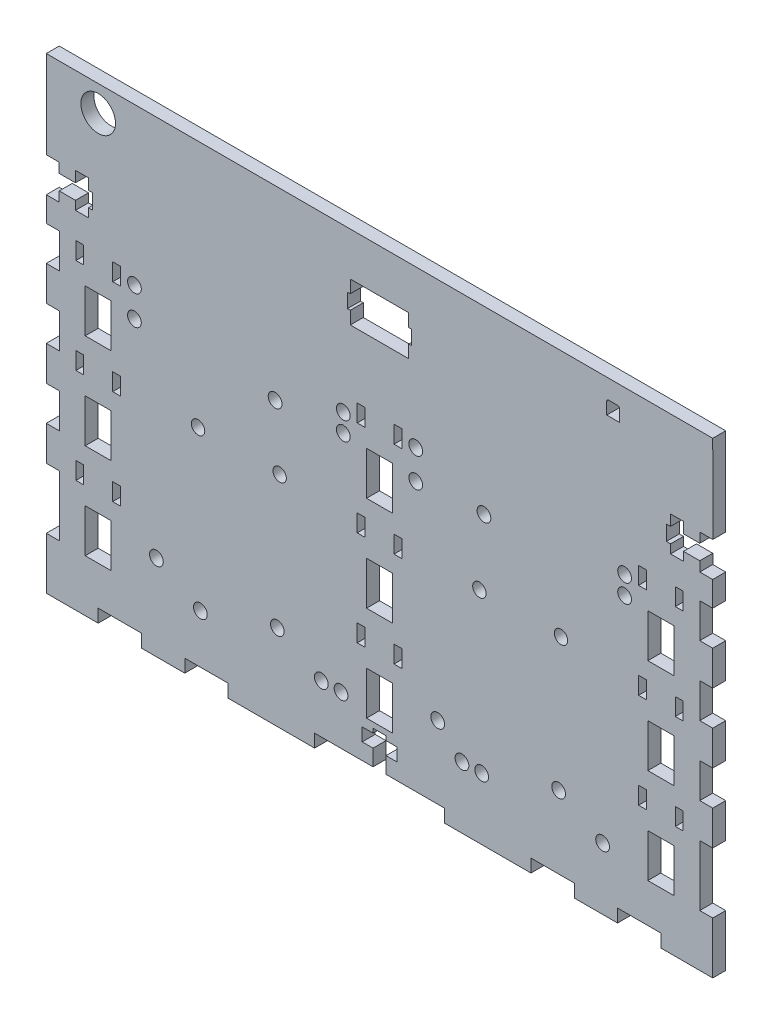
SolidWorks part; units mm, degrees
material "Balsa"
ref_plane "Alzado" through (0, 0, 0) normal (0, 0, 1) x (1, 0, 0)
ref_plane "Planta" through (0, 0, 0) normal (0, 1, 0) x (1, 0, 0)
ref_plane "Vista lateral" through (0, 0, 0) normal (1, 0, 0) x (0, 0, -1)
sketch "Croquis1" plane through (0, 0, 0) normal (0, 0, 1) x (1, 0, 0)
  line L0 (33621.3945, 12954.1794) -> (33621.4126, 12954.1794)
  line L1 (33643.5488, 12968.8076) -> (33643.5488, 12973.6576)
  line L2 (33643.5488, 12973.9576) -> (33643.5488, 12978.8076)
  line L3 (33643.5488, 12978.8076) -> (33646.3988, 12978.8076)
  line L4 (33646.6988, 12978.8076) -> (33649.5488, 12978.8076)
  line L5 (33649.5488, 12978.8076) -> (33649.5488, 12973.9576)
  line L6 (33649.5488, 12973.6576) -> (33649.5488, 12968.8076)
  line L7 (33649.5488, 12968.8076) -> (33646.6988, 12968.8076)
  line L8 (33646.3988, 12968.8076) -> (33643.5488, 12968.8076)
  line L9 (33584.5488, 13000.8076) -> (33584.5488, 12995.9576)
  line L10 (33584.5488, 12995.6576) -> (33584.5488, 12990.8076)
  line L11 (33584.5488, 12990.8076) -> (33581.6988, 12990.8076)
  line L12 (33581.3988, 12990.8076) -> (33578.5488, 12990.8076)
  line L13 (33578.5488, 12990.8076) -> (33578.5488, 12995.6576)
  line L14 (33578.5488, 12995.9576) -> (33578.5488, 13000.8076)
  line L15 (33578.5488, 13000.8076) -> (33581.3988, 13000.8076)
  line L16 (33581.6988, 13000.8076) -> (33584.5488, 13000.8076)
  line L17 (33584.8988, 13008.8076) -> (33585.5512, 13008.8076)
  line L18 (33585.8512, 13008.8076) -> (33586.6988, 13008.8076)
  line L19 (33586.6988, 13008.8076) -> (33586.6988, 13006.8962)
  line L20 (33586.6988, 13006.5962) -> (33586.6988, 13004.8076)
  line L21 (33586.6988, 13004.8076) -> (33585.8512, 13004.8076)
  line L22 (33585.5512, 13004.8076) -> (33584.8988, 13004.8076)
  line L23 (33584.8988, 13004.8076) -> (33584.8988, 13006.5962)
  line L24 (33584.8988, 13006.8962) -> (33584.8988, 13008.8076)
  line L25 (33578.1988, 13004.8076) -> (33577.4254, 13004.8076)
  line L26 (33577.1254, 13004.8076) -> (33576.3988, 13004.8076)
  line L27 (33576.3988, 13004.8076) -> (33576.3988, 13006.7518)
  line L28 (33576.3988, 13007.0518) -> (33576.3988, 13008.8076)
  line L29 (33576.3988, 13008.8076) -> (33577.1254, 13008.8076)
  line L30 (33577.4254, 13008.8076) -> (33578.1988, 13008.8076)
  line L31 (33578.1988, 13008.8076) -> (33578.1988, 13007.0518)
  line L32 (33578.1988, 13006.7518) -> (33578.1988, 13004.8076)
  line L33 (33643.1988, 13004.8076) -> (33642.4254, 13004.8076)
  line L34 (33642.1254, 13004.8076) -> (33641.3988, 13004.8076)
  line L35 (33641.3988, 13004.8076) -> (33641.3988, 13006.7518)
  line L36 (33641.3988, 13007.0518) -> (33641.3988, 13008.8076)
  line L37 (33641.3988, 13008.8076) -> (33642.1254, 13008.8076)
  line L38 (33642.4254, 13008.8076) -> (33643.1988, 13008.8076)
  line L39 (33643.1988, 13008.8076) -> (33643.1988, 13007.0518)
  line L40 (33643.1988, 13006.7518) -> (33643.1988, 13004.8076)
  line L41 (33649.8988, 13008.8076) -> (33650.5512, 13008.8076)
  line L42 (33650.8512, 13008.8076) -> (33651.6988, 13008.8076)
  line L43 (33651.6988, 13008.8076) -> (33651.6988, 13006.8962)
  line L44 (33651.6988, 13006.5962) -> (33651.6988, 13004.8076)
  line L45 (33651.6988, 13004.8076) -> (33650.8512, 13004.8076)
  line L46 (33650.5512, 13004.8076) -> (33649.8988, 13004.8076)
  line L47 (33649.8988, 13004.8076) -> (33649.8988, 13006.5962)
  line L48 (33649.8988, 13006.8962) -> (33649.8988, 13008.8076)
  line L49 (33643.5488, 12990.8076) -> (33643.5488, 12995.6576)
  line L50 (33643.5488, 12995.9576) -> (33643.5488, 13000.8076)
  line L51 (33643.5488, 13000.8076) -> (33646.3988, 13000.8076)
  line L52 (33646.6988, 13000.8076) -> (33649.5488, 13000.8076)
  line L53 (33649.5488, 13000.8076) -> (33649.5488, 12995.9576)
  line L54 (33649.5488, 12995.6576) -> (33649.5488, 12990.8076)
  line L55 (33649.5488, 12990.8076) -> (33646.6988, 12990.8076)
  line L56 (33646.3988, 12990.8076) -> (33643.5488, 12990.8076)
  line L57 (33584.8988, 12986.8076) -> (33585.5512, 12986.8076)
  line L58 (33585.8512, 12986.8076) -> (33586.6988, 12986.8076)
  line L59 (33586.6988, 12986.8076) -> (33586.6988, 12984.8962)
  line L60 (33586.6988, 12984.5962) -> (33586.6988, 12982.8076)
  line L61 (33586.6988, 12982.8076) -> (33585.8512, 12982.8076)
  line L62 (33585.5512, 12982.8076) -> (33584.8988, 12982.8076)
  line L63 (33584.8988, 12982.8076) -> (33584.8988, 12984.5962)
  line L64 (33584.8988, 12984.8962) -> (33584.8988, 12986.8076)
  line L65 (33651.6988, 12960.8076) -> (33650.8512, 12960.8076)
  line L66 (33650.5512, 12960.8076) -> (33649.8988, 12960.8076)
  line L67 (33649.8988, 12960.8076) -> (33649.8988, 12962.5962)
  line L68 (33649.8988, 12962.8962) -> (33649.8988, 12964.8076)
  line L69 (33649.8988, 12964.8076) -> (33650.5512, 12964.8076)
  line L70 (33650.8512, 12964.8076) -> (33651.6988, 12964.8076)
  line L71 (33651.6988, 12964.8076) -> (33651.6988, 12962.8962)
  line L72 (33651.6988, 12962.5962) -> (33651.6988, 12960.8076)
  line L73 (33641.3988, 12964.8076) -> (33642.1254, 12964.8076)
  line L74 (33642.4254, 12964.8076) -> (33643.1988, 12964.8076)
  line L75 (33643.1988, 12964.8076) -> (33643.1988, 12963.0518)
  line L76 (33643.1988, 12962.7518) -> (33643.1988, 12960.8076)
  line L77 (33643.1988, 12960.8076) -> (33642.4254, 12960.8076)
  line L78 (33642.1254, 12960.8076) -> (33641.3988, 12960.8076)
  line L79 (33641.3988, 12960.8076) -> (33641.3988, 12962.7518)
  line L80 (33641.3988, 12963.0518) -> (33641.3988, 12964.8076)
  line L81 (33578.1988, 12982.8076) -> (33577.4254, 12982.8076)
  line L82 (33577.1254, 12982.8076) -> (33576.3988, 12982.8076)
  line L83 (33576.3988, 12982.8076) -> (33576.3988, 12984.7518)
  line L84 (33576.3988, 12985.0518) -> (33576.3988, 12986.8076)
  line L85 (33576.3988, 12986.8076) -> (33577.1254, 12986.8076)
  line L86 (33577.4254, 12986.8076) -> (33578.1988, 12986.8076)
  line L87 (33578.1988, 12986.8076) -> (33578.1988, 12985.0518)
  line L88 (33578.1988, 12984.7518) -> (33578.1988, 12982.8076)
  line L89 (33643.5488, 12956.8076) -> (33646.3988, 12956.8076)
  line L90 (33646.6988, 12956.8076) -> (33649.5488, 12956.8076)
  line L91 (33649.5488, 12956.8076) -> (33649.5488, 12951.9576)
  line L92 (33649.5488, 12951.6576) -> (33649.5488, 12946.8076)
  line L93 (33649.5488, 12946.8076) -> (33646.6988, 12946.8076)
  line L94 (33646.3988, 12946.8076) -> (33643.5488, 12946.8076)
  line L95 (33643.5488, 12946.8076) -> (33643.5488, 12951.6576)
  line L96 (33643.5488, 12951.9576) -> (33643.5488, 12956.8076)
  line L97 (33708.1988, 12960.8076) -> (33707.4254, 12960.8076)
  line L98 (33707.1254, 12960.8076) -> (33706.3988, 12960.8076)
  line L99 (33706.3988, 12960.8076) -> (33706.3988, 12962.7518)
  line L100 (33706.3988, 12963.0518) -> (33706.3988, 12964.8076)
  line L101 (33706.3988, 12964.8076) -> (33707.1254, 12964.8076)
  line L102 (33707.4254, 12964.8076) -> (33708.1988, 12964.8076)
  line L103 (33708.1988, 12964.8076) -> (33708.1988, 12963.0518)
  line L104 (33708.1988, 12962.7518) -> (33708.1988, 12960.8076)
  line L105 (33584.5488, 12946.8076) -> (33581.5488, 12946.8076)
  line L106 (33581.4403, 12946.8076) -> (33578.5488, 12946.8076)
  line L107 (33578.5488, 12946.8076) -> (33578.5488, 12951.7169)
  line L108 (33578.5488, 12951.8983) -> (33578.5488, 12956.8076)
  line L109 (33578.5488, 12956.8076) -> (33581.4403, 12956.8076)
  line L110 (33581.5488, 12956.8076) -> (33584.5488, 12956.8076)
  line L111 (33584.5488, 12956.8076) -> (33584.5488, 12951.8983)
  line L112 (33584.5488, 12951.7169) -> (33584.5488, 12946.8076)
  line L113 (33584.8988, 12964.8076) -> (33585.5512, 12964.8076)
  line L114 (33585.8512, 12964.8076) -> (33586.6988, 12964.8076)
  line L115 (33586.6988, 12964.8076) -> (33586.6988, 12962.8962)
  line L116 (33586.6988, 12962.5962) -> (33586.6988, 12960.8076)
  line L117 (33586.6988, 12960.8076) -> (33585.8512, 12960.8076)
  line L118 (33585.5512, 12960.8076) -> (33584.8988, 12960.8076)
  line L119 (33584.8988, 12960.8076) -> (33584.8988, 12962.5962)
  line L120 (33584.8988, 12962.8962) -> (33584.8988, 12964.8076)
  line L121 (33708.5488, 12956.8076) -> (33711.3988, 12956.8076)
  line L122 (33711.6988, 12956.8076) -> (33714.5488, 12956.8076)
  line L123 (33714.5488, 12956.8076) -> (33714.5488, 12951.9576)
  line L124 (33714.5488, 12951.6576) -> (33714.5488, 12946.8076)
  line L125 (33714.5488, 12946.8076) -> (33711.6988, 12946.8076)
  line L126 (33711.3988, 12946.8076) -> (33708.5488, 12946.8076)
  line L127 (33708.5488, 12946.8076) -> (33708.5488, 12951.6576)
  line L128 (33708.5488, 12951.9576) -> (33708.5488, 12956.8076)
  line L129 (33578.1988, 12960.8076) -> (33577.4254, 12960.8076)
  line L130 (33577.1254, 12960.8076) -> (33576.3988, 12960.8076)
  line L131 (33576.3988, 12960.8076) -> (33576.3988, 12962.7518)
  line L132 (33576.3988, 12963.0518) -> (33576.3988, 12964.8076)
  line L133 (33576.3988, 12964.8076) -> (33577.1254, 12964.8076)
  line L134 (33577.4254, 12964.8076) -> (33578.1988, 12964.8076)
  line L135 (33578.1988, 12964.8076) -> (33578.1988, 12963.0518)
  line L136 (33578.1988, 12962.7518) -> (33578.1988, 12960.8076)
  line L137 (33714.8988, 12964.8076) -> (33715.5512, 12964.8076)
  line L138 (33715.8512, 12964.8076) -> (33716.6988, 12964.8076)
  line L139 (33716.6988, 12964.8076) -> (33716.6988, 12962.8962)
  line L140 (33716.6988, 12962.5962) -> (33716.6988, 12960.8076)
  line L141 (33716.6988, 12960.8076) -> (33715.8512, 12960.8076)
  line L142 (33715.5512, 12960.8076) -> (33714.8988, 12960.8076)
  line L143 (33714.8988, 12960.8076) -> (33714.8988, 12962.5962)
  line L144 (33714.8988, 12962.8962) -> (33714.8988, 12964.8076)
  line L145 (33723.5488, 12976.8076) -> (33720.5488, 12976.8076)
  line L146 (33723.5488, 12984.8076) -> (33723.5488, 12976.8076)
  line L147 (33723.5488, 12984.8076) -> (33720.5488, 12984.8076)
  line L148 (33720.5488, 12984.8076) -> (33720.5488, 12992.8076)
  line L149 (33572.5488, 12976.8076) -> (33572.5488, 12968.8076)
  line L150 (33723.5488, 12992.8076) -> (33720.5488, 12992.8076)
  line L151 (33723.5488, 13000.8076) -> (33723.5488, 12992.8076)
  line L152 (33723.5488, 13000.8076) -> (33720.5488, 13000.8076)
  line L153 (33720.5488, 13000.8076) -> (33720.5488, 13008.8076)
  line L154 (33723.5488, 13008.8076) -> (33720.5488, 13008.8076)
  line L155 (33723.5488, 13014.5511) -> (33723.5488, 13008.8076)
  line L156 (33723.5503, 13022.5518) -> (33723.5488, 13042.8076)
  line L157 (33569.5488, 13042.8076) -> (33723.5488, 13042.8076)
  line L158 (33572.5488, 13000.8076) -> (33572.5488, 13008.8076)
  line L159 (33569.5488, 13000.8076) -> (33572.5488, 13000.8076)
  line L160 (33569.5488, 13000.8076) -> (33569.5488, 12992.8076)
  line L161 (33569.5488, 12992.8076) -> (33572.5488, 12992.8076)
  line L162 (33572.5488, 12984.8076) -> (33572.5488, 12992.8076)
  line L163 (33572.5484, 13014.5511) -> (33572.5481, 13016.8076)
  line L164 (33569.5488, 12984.8076) -> (33572.5488, 12984.8076)
  line L165 (33569.5488, 12984.8076) -> (33569.5488, 12976.8076)
  line L166 (33569.5488, 12976.8076) -> (33572.5488, 12976.8076)
  line L167 (33572.5488, 12960.8076) -> (33572.5488, 12946.8076)
  line L168 (33601.5488, 12937.8076) -> (33611.5488, 12937.8076)
  line L169 (33569.5488, 12968.8076) -> (33572.5488, 12968.8076)
  line L170 (33569.5488, 12968.8076) -> (33569.5488, 12960.8076)
  line L171 (33569.5488, 12960.8076) -> (33572.5488, 12960.8076)
  line L172 (33681.665, 12937.8076) -> (33681.965, 12937.8076)
  line L174 (33569.5488, 12946.8076) -> (33572.5488, 12946.8076)
  line L175 (33569.5488, 12946.8076) -> (33569.5488, 12934.8076)
  line L176 (33569.5488, 12934.8076) -> (33581.5488, 12934.8076)
  line L177 (33581.5488, 12934.8076) -> (33581.5488, 12937.8076)
  line L178 (33591.5488, 12937.8076) -> (33581.5488, 12937.8076)
  line L179 (33591.5488, 12934.8076) -> (33591.5488, 12937.8076)
  line L180 (33591.5488, 12934.8076) -> (33601.5488, 12934.8076)
  line L181 (33601.5488, 12934.8076) -> (33601.5488, 12937.8076)
  line L184 (33631.5488, 12934.8076) -> (33631.5488, 12937.8076)
  line L187 (33661.5488, 12934.8076) -> (33661.5488, 12937.8076)
  line L188 (33645.0488, 12937.8076) -> (33645.0488, 12941.5576)
  line L189 (33645.0488, 12941.5576) -> (33642.5488, 12941.5576)
  line L190 (33642.5488, 12941.5576) -> (33642.5488, 12944.5576)
  line L191 (33645.0488, 12944.5576) -> (33642.5488, 12944.5576)
  line L192 (33645.0488, 12944.5576) -> (33645.0488, 12945.5376)
  line L193 (33648.0488, 12945.5376) -> (33645.0488, 12945.5376)
  line L194 (33648.0488, 12944.5576) -> (33648.0488, 12945.5376)
  line L195 (33650.5488, 12944.5576) -> (33648.0488, 12944.5576)
  line L196 (33650.5488, 12941.5576) -> (33650.5488, 12944.5576)
  line L197 (33650.5488, 12941.5576) -> (33648.0488, 12941.5576)
  line L198 (33648.0488, 12937.8076) -> (33648.0488, 12941.5576)
  line L199 (33681.5488, 12937.8076) -> (33681.665, 12937.8076)
  line L200 (33681.965, 12937.8076) -> (33691.5488, 12937.8076)
  line L201 (33691.5488, 12934.8076) -> (33691.5488, 12937.8076)
  line L202 (33691.5488, 12934.8076) -> (33701.5488, 12934.8076)
  line L203 (33701.5488, 12934.8076) -> (33701.5488, 12937.8076)
  line L204 (33701.5488, 12937.8076) -> (33711.5488, 12937.8076)
  line L205 (33711.5488, 12934.8076) -> (33711.5488, 12937.8076)
  line L206 (33711.5488, 12934.8076) -> (33723.5488, 12934.8076)
  line L207 (33723.5488, 12946.8076) -> (33723.5488, 12934.8076)
  line L208 (33723.5488, 12946.8076) -> (33720.5488, 12946.8076)
  line L209 (33720.5488, 12960.8076) -> (33720.5488, 12952.7511)
  line L210 (33720.5488, 12952.4511) -> (33720.5488, 12946.8076)
  line L211 (33723.5488, 12960.8076) -> (33720.5488, 12960.8076)
  line L212 (33723.5488, 12968.8076) -> (33723.5488, 12960.8076)
  line L213 (33723.5488, 12968.8076) -> (33720.5488, 12968.8076)
  line L214 (33702.0488, 13037.9076) -> (33702.0488, 13035.2076)
  line L215 (33699.0488, 13035.2076) -> (33702.0488, 13035.2076)
  line L216 (33699.0488, 13037.9076) -> (33699.0488, 13035.2076)
  line L217 (33699.5488, 13038.4076) -> (33701.5488, 13038.4076)
  line L218 (33639.7988, 13032.8076) -> (33653.2988, 13032.8076)
  line L219 (33653.2988, 13032.8076) -> (33653.2988, 13029.8576)
  line L220 (33653.2988, 13029.8576) -> (33653.9488, 13029.8576)
  line L221 (33653.9488, 13029.8576) -> (33653.9488, 13026.5576)
  line L222 (33653.2988, 13026.5576) -> (33653.9488, 13026.5576)
  line L223 (33653.2988, 13026.5576) -> (33653.2988, 13023.6076)
  line L224 (33639.7988, 13023.6076) -> (33653.2988, 13023.6076)
  line L225 (33639.7988, 13026.5576) -> (33639.7988, 13023.6076)
  line L226 (33639.1488, 13026.5576) -> (33639.7988, 13026.5576)
  line L227 (33639.1488, 13029.8576) -> (33639.1488, 13026.5576)
  line L228 (33639.1488, 13029.8576) -> (33639.7988, 13029.8576)
  line L229 (33639.7988, 13032.8076) -> (33639.7988, 13029.8576)
  line L230 (33611.5488, 12937.8076) -> (33611.5488, 12934.8076)
  line L231 (33611.5488, 12934.8076) -> (33631.5488, 12934.8076)
  line L232 (33631.5488, 12937.8076) -> (33645.0488, 12937.8076)
  line L233 (33648.0488, 12937.8076) -> (33661.5488, 12937.8076)
  line L234 (33681.5488, 12934.8076) -> (33681.5488, 12937.8076)
  line L235 (33681.5488, 12934.8076) -> (33661.5488, 12934.8076)
  line L237 (33578.5488, 12968.8076) -> (33578.5488, 12973.6576)
  line L238 (33578.5488, 12973.9576) -> (33578.5488, 12978.8076)
  line L239 (33578.5488, 12978.8076) -> (33581.3988, 12978.8076)
  line L240 (33581.6988, 12978.8076) -> (33584.5488, 12978.8076)
  line L241 (33584.5488, 12978.8076) -> (33584.5488, 12973.9576)
  line L242 (33584.5488, 12973.6576) -> (33584.5488, 12968.8076)
  line L243 (33584.5488, 12968.8076) -> (33581.6988, 12968.8076)
  line L244 (33581.3988, 12968.8076) -> (33578.5488, 12968.8076)
  line L245 (33649.8988, 12986.8076) -> (33650.5512, 12986.8076)
  line L246 (33650.8512, 12986.8076) -> (33651.6988, 12986.8076)
  line L247 (33651.6988, 12986.8076) -> (33651.6988, 12984.8962)
  line L248 (33651.6988, 12984.5962) -> (33651.6988, 12982.8076)
  line L249 (33651.6988, 12982.8076) -> (33650.8512, 12982.8076)
  line L250 (33650.5512, 12982.8076) -> (33649.8988, 12982.8076)
  line L251 (33649.8988, 12982.8076) -> (33649.8988, 12984.5962)
  line L252 (33649.8988, 12984.8962) -> (33649.8988, 12986.8076)
  line L253 (33643.1988, 12982.8076) -> (33642.4254, 12982.8076)
  line L254 (33642.1254, 12982.8076) -> (33641.3988, 12982.8076)
  line L255 (33641.3988, 12982.8076) -> (33641.3988, 12984.7518)
  line L256 (33641.3988, 12985.0518) -> (33641.3988, 12986.8076)
  line L257 (33641.3988, 12986.8076) -> (33642.1254, 12986.8076)
  line L258 (33642.4254, 12986.8076) -> (33643.1988, 12986.8076)
  line L259 (33643.1988, 12986.8076) -> (33643.1988, 12985.0518)
  line L260 (33643.1988, 12984.7518) -> (33643.1988, 12982.8076)
  line L261 (33720.5488, 12968.8076) -> (33720.5488, 12976.8076)
  line L286 (33714.8988, 12986.8076) -> (33715.5512, 12986.8076)
  line L287 (33715.8512, 12986.8076) -> (33716.6988, 12986.8076)
  line L288 (33716.6988, 12986.8076) -> (33716.6988, 12984.8962)
  line L289 (33716.6988, 12984.5962) -> (33716.6988, 12982.8076)
  line L290 (33716.6988, 12982.8076) -> (33715.8512, 12982.8076)
  line L291 (33715.5512, 12982.8076) -> (33714.8988, 12982.8076)
  line L292 (33714.8988, 12982.8076) -> (33714.8988, 12984.5962)
  line L293 (33714.8988, 12984.8962) -> (33714.8988, 12986.8076)
  line L294 (33708.1988, 12982.8076) -> (33707.4254, 12982.8076)
  line L295 (33707.1254, 12982.8076) -> (33706.3988, 12982.8076)
  line L296 (33706.3988, 12982.8076) -> (33706.3988, 12984.7518)
  line L297 (33706.3988, 12985.0518) -> (33706.3988, 12986.8076)
  line L298 (33706.3988, 12986.8076) -> (33707.1254, 12986.8076)
  line L299 (33707.4254, 12986.8076) -> (33708.1988, 12986.8076)
  line L300 (33708.1988, 12986.8076) -> (33708.1988, 12985.0518)
  line L301 (33708.1988, 12984.7518) -> (33708.1988, 12982.8076)
  line L302 (33708.5488, 12968.8076) -> (33708.5488, 12973.6576)
  line L303 (33708.5488, 12973.9576) -> (33708.5488, 12978.8076)
  line L304 (33708.5488, 12978.8076) -> (33711.3988, 12978.8076)
  line L305 (33711.6988, 12978.8076) -> (33714.5488, 12978.8076)
  line L306 (33714.5488, 12978.8076) -> (33714.5488, 12973.9576)
  line L307 (33714.5488, 12973.6576) -> (33714.5488, 12968.8076)
  line L308 (33714.5488, 12968.8076) -> (33711.6988, 12968.8076)
  line L309 (33711.3988, 12968.8076) -> (33708.5488, 12968.8076)
  line L310 (33720.5495, 13020.3018) -> (33720.5498, 13022.5518)
  line L311 (33720.5493, 13014.5511) -> (33720.5495, 13016.8076)
  line L313 (33723.5488, 13014.5511) -> (33720.5493, 13014.5511)
  line L315 (33723.5503, 13022.5518) -> (33720.5498, 13022.5518)
  line L316 (33720.5495, 13020.3018) -> (33716.7995, 13020.3018)
  line L317 (33716.7995, 13022.7997) -> (33716.7995, 13020.3018)
  line L318 (33716.7995, 13022.7997) -> (33713.7995, 13022.7997)
  line L319 (33713.7995, 13022.7997) -> (33713.7995, 13020.3018)
  line L320 (33713.7995, 13020.3018) -> (33712.8195, 13020.3018)
  line L321 (33712.8195, 13020.3018) -> (33712.8195, 13016.8076)
  line L322 (33713.7995, 13016.8076) -> (33712.8195, 13016.8076)
  line L323 (33713.7995, 13016.8076) -> (33713.7995, 13014.7997)
  line L324 (33716.7995, 13014.7997) -> (33713.7995, 13014.7997)
  line L325 (33716.7995, 13016.8076) -> (33716.7995, 13014.7997)
  line L326 (33720.5495, 13016.8076) -> (33716.7995, 13016.8076)
  line L328 (33569.5488, 13008.8076) -> (33572.5488, 13008.8076)
  line L329 (33569.5488, 13014.5511) -> (33569.5488, 13008.8076)
  line L330 (33569.5488, 13042.8076) -> (33569.5474, 13022.5518)
  line L332 (33572.5481, 13020.3018) -> (33572.5478, 13022.5518)
  line L334 (33569.5488, 13014.5511) -> (33572.5484, 13014.5511)
  line L336 (33569.5474, 13022.5518) -> (33572.5478, 13022.5518)
  line L337 (33572.5481, 13020.3018) -> (33576.2981, 13020.3018)
  line L338 (33576.2981, 13022.7997) -> (33576.2981, 13020.3018)
  line L339 (33576.2981, 13022.7997) -> (33579.2981, 13022.7997)
  line L340 (33579.2981, 13022.7997) -> (33579.2981, 13020.3018)
  line L341 (33579.2981, 13020.3018) -> (33580.2781, 13020.3018)
  line L342 (33580.2781, 13020.3018) -> (33580.2781, 13016.8076)
  line L343 (33579.2981, 13016.8076) -> (33580.2781, 13016.8076)
  line L344 (33579.2981, 13016.8076) -> (33579.2981, 13014.7997)
  line L345 (33576.2981, 13014.7997) -> (33579.2981, 13014.7997)
  line L346 (33576.2981, 13016.8076) -> (33576.2981, 13014.7997)
  line L347 (33572.5481, 13016.8076) -> (33576.2981, 13016.8076)
  line L349 (33576.3988, 13004.8076) -> (33578.1988, 13004.8076)
  line L350 (33578.1988, 13004.8076) -> (33578.1988, 13008.8076)
  line L351 (33578.1988, 13008.8076) -> (33576.3988, 13008.8076)
  line L352 (33576.3988, 13008.8076) -> (33576.3988, 13004.8076)
  line L353 (33584.8988, 13004.8076) -> (33586.6988, 13004.8076)
  line L354 (33586.6988, 13004.8076) -> (33586.6988, 13008.8076)
  line L355 (33586.6988, 13008.8076) -> (33584.8988, 13008.8076)
  line L356 (33584.8988, 13008.8076) -> (33584.8988, 13004.8076)
  line L357 (33578.5488, 12990.8076) -> (33584.5488, 12990.8076)
  line L358 (33584.5488, 12990.8076) -> (33584.5488, 13000.8076)
  line L359 (33584.5488, 13000.8076) -> (33578.5488, 13000.8076)
  line L360 (33578.5488, 13000.8076) -> (33578.5488, 12990.8076)
  line L361 (33576.3988, 12982.8076) -> (33578.1988, 12982.8076)
  line L362 (33578.1988, 12982.8076) -> (33578.1988, 12986.8076)
  line L363 (33578.1988, 12986.8076) -> (33576.3988, 12986.8076)
  line L364 (33576.3988, 12986.8076) -> (33576.3988, 12982.8076)
  line L365 (33584.8988, 12982.8076) -> (33586.6988, 12982.8076)
  line L366 (33586.6988, 12982.8076) -> (33586.6988, 12986.8076)
  line L367 (33586.6988, 12986.8076) -> (33584.8988, 12986.8076)
  line L368 (33584.8988, 12986.8076) -> (33584.8988, 12982.8076)
  line L369 (33578.5488, 12968.8076) -> (33584.5488, 12968.8076)
  line L370 (33584.5488, 12968.8076) -> (33584.5488, 12978.8076)
  line L371 (33584.5488, 12978.8076) -> (33578.5488, 12978.8076)
  line L372 (33578.5488, 12978.8076) -> (33578.5488, 12968.8076)
  line L373 (33576.3988, 12960.8076) -> (33578.1988, 12960.8076)
  line L374 (33578.1988, 12960.8076) -> (33578.1988, 12964.8076)
  line L375 (33578.1988, 12964.8076) -> (33576.3988, 12964.8076)
  line L376 (33576.3988, 12964.8076) -> (33576.3988, 12960.8076)
  line L377 (33584.8988, 12960.8076) -> (33586.6988, 12960.8076)
  line L378 (33586.6988, 12960.8076) -> (33586.6988, 12964.8076)
  line L379 (33586.6988, 12964.8076) -> (33584.8988, 12964.8076)
  line L380 (33584.8988, 12964.8076) -> (33584.8988, 12960.8076)
  line L381 (33578.5488, 12956.8076) -> (33584.5488, 12956.8076)
  line L382 (33584.5488, 12956.8076) -> (33584.5488, 12946.8076)
  line L383 (33584.5488, 12946.8076) -> (33578.5488, 12946.8076)
  line L384 (33578.5488, 12946.8076) -> (33578.5488, 12956.8076)
  line L388 (33720.5488, 12952.4511) -> (33720.5488, 12952.7511)
  line L390 (33641.3988, 13004.8076) -> (33643.1988, 13004.8076)
  line L391 (33643.1988, 13004.8076) -> (33643.1988, 13008.8076)
  line L392 (33643.1988, 13008.8076) -> (33641.3988, 13008.8076)
  line L393 (33641.3988, 13008.8076) -> (33641.3988, 13004.8076)
  line L394 (33649.8988, 13004.8076) -> (33651.6988, 13004.8076)
  line L395 (33651.6988, 13004.8076) -> (33651.6988, 13008.8076)
  line L396 (33651.6988, 13008.8076) -> (33649.8988, 13008.8076)
  line L397 (33649.8988, 13008.8076) -> (33649.8988, 13004.8076)
  line L398 (33643.5488, 12990.8076) -> (33649.5488, 12990.8076)
  line L399 (33649.5488, 12990.8076) -> (33649.5488, 13000.8076)
  line L400 (33649.5488, 13000.8076) -> (33643.5488, 13000.8076)
  line L401 (33643.5488, 13000.8076) -> (33643.5488, 12990.8076)
  line L402 (33641.3988, 12982.8076) -> (33643.1988, 12982.8076)
  line L403 (33643.1988, 12982.8076) -> (33643.1988, 12986.8076)
  line L404 (33643.1988, 12986.8076) -> (33641.3988, 12986.8076)
  line L405 (33641.3988, 12986.8076) -> (33641.3988, 12982.8076)
  line L406 (33649.8988, 12982.8076) -> (33651.6988, 12982.8076)
  line L407 (33651.6988, 12982.8076) -> (33651.6988, 12986.8076)
  line L408 (33651.6988, 12986.8076) -> (33649.8988, 12986.8076)
  line L409 (33649.8988, 12986.8076) -> (33649.8988, 12982.8076)
  line L410 (33643.5488, 12968.8076) -> (33649.5488, 12968.8076)
  line L411 (33649.5488, 12968.8076) -> (33649.5488, 12978.8076)
  line L412 (33649.5488, 12978.8076) -> (33643.5488, 12978.8076)
  line L413 (33643.5488, 12978.8076) -> (33643.5488, 12968.8076)
  line L414 (33641.3988, 12960.8076) -> (33643.1988, 12960.8076)
  line L415 (33643.1988, 12960.8076) -> (33643.1988, 12964.8076)
  line L416 (33643.1988, 12964.8076) -> (33641.3988, 12964.8076)
  line L417 (33641.3988, 12964.8076) -> (33641.3988, 12960.8076)
  line L418 (33649.8988, 12960.8076) -> (33651.6988, 12960.8076)
  line L419 (33651.6988, 12960.8076) -> (33651.6988, 12964.8076)
  line L420 (33651.6988, 12964.8076) -> (33649.8988, 12964.8076)
  line L421 (33649.8988, 12964.8076) -> (33649.8988, 12960.8076)
  line L422 (33643.5488, 12946.8076) -> (33649.5488, 12946.8076)
  line L423 (33649.5488, 12946.8076) -> (33649.5488, 12956.8076)
  line L424 (33649.5488, 12956.8076) -> (33643.5488, 12956.8076)
  line L425 (33643.5488, 12956.8076) -> (33643.5488, 12946.8076)
  line L426 (33706.3988, 13004.8076) -> (33708.1988, 13004.8076)
  line L427 (33708.1988, 13004.8076) -> (33708.1988, 13008.8076)
  line L428 (33708.1988, 13008.8076) -> (33706.3988, 13008.8076)
  line L429 (33706.3988, 13008.8076) -> (33706.3988, 13004.8076)
  line L430 (33714.8988, 13004.8076) -> (33716.6988, 13004.8076)
  line L431 (33716.6988, 13004.8076) -> (33716.6988, 13008.8076)
  line L432 (33716.6988, 13008.8076) -> (33714.8988, 13008.8076)
  line L433 (33714.8988, 13008.8076) -> (33714.8988, 13004.8076)
  line L434 (33708.5488, 12990.8076) -> (33714.5488, 12990.8076)
  line L435 (33714.5488, 12990.8076) -> (33714.5488, 13000.8076)
  line L436 (33714.5488, 13000.8076) -> (33708.5488, 13000.8076)
  line L437 (33708.5488, 13000.8076) -> (33708.5488, 12990.8076)
  line L438 (33706.3988, 12982.8076) -> (33708.1988, 12982.8076)
  line L439 (33708.1988, 12982.8076) -> (33708.1988, 12986.8076)
  line L440 (33708.1988, 12986.8076) -> (33706.3988, 12986.8076)
  line L441 (33706.3988, 12986.8076) -> (33706.3988, 12982.8076)
  line L442 (33714.8988, 12982.8076) -> (33716.6988, 12982.8076)
  line L443 (33716.6988, 12982.8076) -> (33716.6988, 12986.8076)
  line L444 (33716.6988, 12986.8076) -> (33714.8988, 12986.8076)
  line L445 (33714.8988, 12986.8076) -> (33714.8988, 12982.8076)
  line L446 (33708.5488, 12968.8076) -> (33714.5488, 12968.8076)
  line L447 (33714.5488, 12968.8076) -> (33714.5488, 12978.8076)
  line L448 (33714.5488, 12978.8076) -> (33708.5488, 12978.8076)
  line L449 (33708.5488, 12978.8076) -> (33708.5488, 12968.8076)
  line L450 (33714.8988, 12960.8076) -> (33716.6988, 12960.8076)
  line L451 (33716.6988, 12960.8076) -> (33716.6988, 12964.8076)
  line L452 (33716.6988, 12964.8076) -> (33714.8988, 12964.8076)
  line L453 (33714.8988, 12964.8076) -> (33714.8988, 12960.8076)
  line L454 (33706.3988, 12960.8076) -> (33708.1988, 12960.8076)
  line L455 (33708.1988, 12960.8076) -> (33708.1988, 12964.8076)
  line L456 (33708.1988, 12964.8076) -> (33706.3988, 12964.8076)
  line L457 (33706.3988, 12964.8076) -> (33706.3988, 12960.8076)
  line L458 (33708.5488, 12946.8076) -> (33714.5488, 12946.8076)
  line L459 (33714.5488, 12946.8076) -> (33714.5488, 12956.8076)
  line L460 (33714.5488, 12956.8076) -> (33708.5488, 12956.8076)
  line L461 (33708.5488, 12956.8076) -> (33708.5488, 12946.8076)
  arc A0 (33605.973, 12950.4404) -> (33606.2022, 12947.8811) centre (33605.1588, 12949.0776) ccw
  arc A1 (33606.4094, 12948.0998) -> (33606.2077, 12950.2693) centre (33605.1588, 12949.0776) ccw
  arc A2 (33638.5927, 12950.3614) -> (33638.7862, 12947.9599) centre (33637.6588, 12949.0776) ccw
  arc A3 (33638.9813, 12948.1994) -> (33638.8138, 12950.1667) centre (33637.6588, 12949.0776) ccw
  arc A4 (33666.5087, 12950.3785) -> (33664.0223, 12948.8913) centre (33665.5988, 12949.0776) ccw
  arc A5 (33666.7818, 12948.019) -> (33666.7326, 12950.1888) centre (33665.5988, 12949.0776) ccw
  arc A6 (33664.0841, 12948.6025) -> (33666.5646, 12947.8176) centre (33665.5988, 12949.0776) ccw
  arc A7 (33671.4312, 13002.5455) -> (33669.0968, 13001.0157) centre (33670.6788, 13001.1476) ccw
  arc A8 (33671.7672, 12999.9919) -> (33671.6724, 13002.3857) centre (33670.6788, 13001.1476) ccw
  arc A9 (33669.1481, 13000.7269) -> (33671.5374, 12999.8123) centre (33670.6788, 13001.1476) ccw
  arc A12 (33670.546, 12950.6171) -> (33668.5996, 12949.3759) centre (33670.1588, 12949.0776) ccw
  arc A13 (33671.2791, 12947.9528) -> (33670.823, 12950.5194) centre (33670.1588, 12949.0776) ccw
  arc A14 (33668.5714, 12949.0871) -> (33671.0534, 12947.7661) centre (33670.1588, 12949.0776) ccw
  arc A15 (33698.9811, 12950.3973) -> (33699.1028, 12947.8479) centre (33698.0988, 12949.0776) ccw
  arc A16 (33699.3152, 12948.0575) -> (33699.2082, 12950.2131) centre (33698.0988, 12949.0776) ccw
  arc A17 (33633.9904, 12950.3911) -> (33631.5223, 12948.8913) centre (33633.0988, 12949.0776) ccw
  arc A18 (33634.2662, 12948.0017) -> (33634.2164, 12950.205) centre (33633.0988, 12949.0776) ccw
  arc A19 (33631.5841, 12948.6025) -> (33634.0468, 12947.8042) centre (33633.0988, 12949.0776) ccw
  arc A20 (33655.7902, 13001.2046) -> (33655.9837, 12998.7002) centre (33654.9188, 12999.8776) ccw
  arc A21 (33656.1879, 12998.9239) -> (33656.0185, 13001.0225) centre (33654.9188, 12999.8776) ccw
  arc A22 (33639.4222, 13000.1606) -> (33639.3253, 13002.2457) centre (33638.1788, 13001.1476) ccw
  arc A23 (33639.103, 13002.4383) -> (33639.2139, 12999.9439) centre (33638.1788, 13001.1476) ccw
  arc A24 (33590.8435, 13001.168) -> (33591.1007, 12998.8177) centre (33589.9188, 12999.8776) ccw
  arc A25 (33591.287, 12999.0725) -> (33591.0657, 13000.9752) centre (33589.9188, 12999.8776) ccw
  arc A29 (33689.2053, 12986.9041) -> (33686.9249, 12985.4809) centre (33688.4738, 12985.5376) ccw
  arc A30 (33689.5962, 12984.4686) -> (33689.4466, 12986.7443) centre (33688.4738, 12985.5376) ccw
  arc A31 (33686.9628, 12985.1922) -> (33689.3741, 12984.2758) centre (33688.4738, 12985.5376) ccw
  arc A32 (33670.8945, 12984.6499) -> (33670.6752, 12986.6765) centre (33669.6238, 12985.5376) ccw
  arc A33 (33670.4436, 12986.853) -> (33670.6952, 12984.4175) centre (33669.6238, 12985.5376) ccw
  arc A34 (33624.2777, 12986.8628) -> (33621.9344, 12985.3567) centre (33623.4738, 12985.5376) ccw
  arc A35 (33624.5666, 12984.4383) -> (33624.511, 12986.6894) centre (33623.4738, 12985.5376) ccw
  arc A36 (33621.9967, 12985.068) -> (33624.3404, 12984.2524) centre (33623.4738, 12985.5376) ccw
  arc A37 (33605.3074, 12986.9287) -> (33603.0785, 12985.6576) centre (33604.6238, 12985.5376) ccw
  arc A38 (33605.8317, 12984.5662) -> (33605.5536, 12986.7777) centre (33604.6238, 12985.5376) ccw
  arc A39 (33603.083, 12985.3688) -> (33605.622, 12984.3518) centre (33604.6238, 12985.5376) ccw
  arc A40 (33595.54, 12956.06) -> (33593.4114, 12954.5788) centre (33594.9988, 12954.5676) ccw
  arc A41 (33596.0207, 12953.3527) -> (33595.8023, 12955.9368) centre (33594.9988, 12954.5676) ccw
  arc A42 (33593.4358, 12954.29) -> (33595.7829, 12953.1872) centre (33594.9988, 12954.5676) ccw
  arc A43 (33655.7879, 13007.9661) -> (33653.3446, 13006.4324) centre (33654.9188, 13006.6376) ccw
  arc A44 (33656.0532, 13005.527) -> (33656.0165, 13007.7844) centre (33654.9188, 13006.6376) ccw
  arc A45 (33653.4101, 13006.1436) -> (33655.8294, 13005.3372) centre (33654.9188, 13006.6376) ccw
  arc A46 (33590.6918, 13008.0242) -> (33588.3323, 13006.6928) centre (33589.9188, 13006.6376) ccw
  arc A47 (33591.1569, 13005.6439) -> (33590.9309, 13007.8607) centre (33589.9188, 13006.6376) ccw
  arc A48 (33588.3486, 13006.404) -> (33590.9477, 13005.4286) centre (33589.9188, 13006.6376) ccw
  arc A49 (33639.0249, 13006.7108) -> (33636.605, 13005.1594) centre (33638.1788, 13005.3676) ccw
  arc A50 (33639.2911, 13004.2348) -> (33639.2561, 13006.5336) centre (33638.1788, 13005.3676) ccw
  arc A51 (33636.6711, 13004.8706) -> (33639.0643, 13004.05) centre (33638.1788, 13005.3676) ccw
  arc A55 (33688.8269, 12955.8834) -> (33689.0887, 12953.4731) centre (33687.9388, 12954.5676) ccw
  arc A56 (33689.2804, 12953.7188) -> (33689.0534, 12955.6981) centre (33687.9388, 12954.5676) ccw
  arc A57 (33660.876, 12955.8907) -> (33658.4199, 12954.4031) centre (33659.9988, 12954.5676) ccw
  arc A58 (33661.1694, 12953.4952) -> (33661.1037, 12955.7075) centre (33659.9988, 12954.5676) ccw
  arc A59 (33658.4774, 12954.1143) -> (33660.9504, 12953.2969) centre (33659.9988, 12954.5676) ccw
  arc A60 (33623.7996, 12955.8864) -> (33621.3671, 12954.4682) centre (33622.9388, 12954.5676) ccw
  arc A61 (33624.1397, 12953.5488) -> (33624.0282, 12955.7048) centre (33622.9388, 12954.5676) ccw
  arc A62 (33621.4126, 12954.1794) -> (33623.9263, 12953.3408) centre (33622.9388, 12954.5676) ccw
  circle A63 centre (33581.5488, 13036.8076) radius 4
  arc A64 (33702.0488, 13037.9076) -> (33701.5488, 13038.4076) centre (33701.5488, 13037.9076) ccw
  arc A65 (33699.5488, 13038.4076) -> (33699.0488, 13037.9076) centre (33699.5488, 13037.9076) ccw
  circle A66 centre (33594.9988, 12954.5676) radius 1.5875
  circle A67 centre (33605.1588, 12949.0776) radius 1.5875
  circle A68 centre (33622.9388, 12954.5676) radius 1.5748
  circle A69 centre (33633.0988, 12949.0776) radius 1.5875
  circle A70 centre (33637.6588, 12949.0776) radius 1.5875
  circle A71 centre (33604.6238, 12985.5376) radius 1.55
  circle A72 centre (33623.4738, 12985.5376) radius 1.55
  circle A73 centre (33589.9188, 12999.8776) radius 1.5875
  circle A74 centre (33589.9188, 13006.6376) radius 1.5875
  circle A75 centre (33622.4188, 12999.8776) radius 1.5875
  circle A76 centre (33638.1788, 13005.3676) radius 1.5875
  circle A77 centre (33638.1788, 13001.1476) radius 1.5875
  circle A78 centre (33659.9988, 12954.5676) radius 1.5875
  circle A79 centre (33665.5988, 12949.0776) radius 1.5875
  circle A80 centre (33670.1588, 12949.0776) radius 1.5875
  circle A81 centre (33669.6238, 12985.5376) radius 1.55
  circle A82 centre (33654.9188, 12999.8776) radius 1.5875
  circle A83 centre (33654.9188, 13006.6376) radius 1.5875
  circle A84 centre (33670.6788, 13001.1476) radius 1.5875
  circle A85 centre (33688.4738, 12985.5376) radius 1.55
  circle A86 centre (33687.9388, 12954.5676) radius 1.5875
  circle A87 centre (33698.0988, 12949.0776) radius 1.5875
  circle A88 centre (33703.1788, 13005.3676) radius 1.5875
  circle A89 centre (33703.1788, 13001.1476) radius 1.5875
  dimension "D1" = 154
  dimension "D2" = 108
extrude "Saliente-Extruir1" add sketch "Croquis1" along normal blind 3 contours L210 L388 L209 L211 L212 L213 L261 L145 L146 L147 L148 L150 L151 L152 L153 L154 L155 L313 L311 L326 L325 L324 L323 L322 L321 L320 L319 L318 L317 L316 L310 L315 L156 L157 L330 L336 L332 L337 L338 L339 L340 L341 L342 L343 L344 L345 L346 L347 L163 L334 L329
